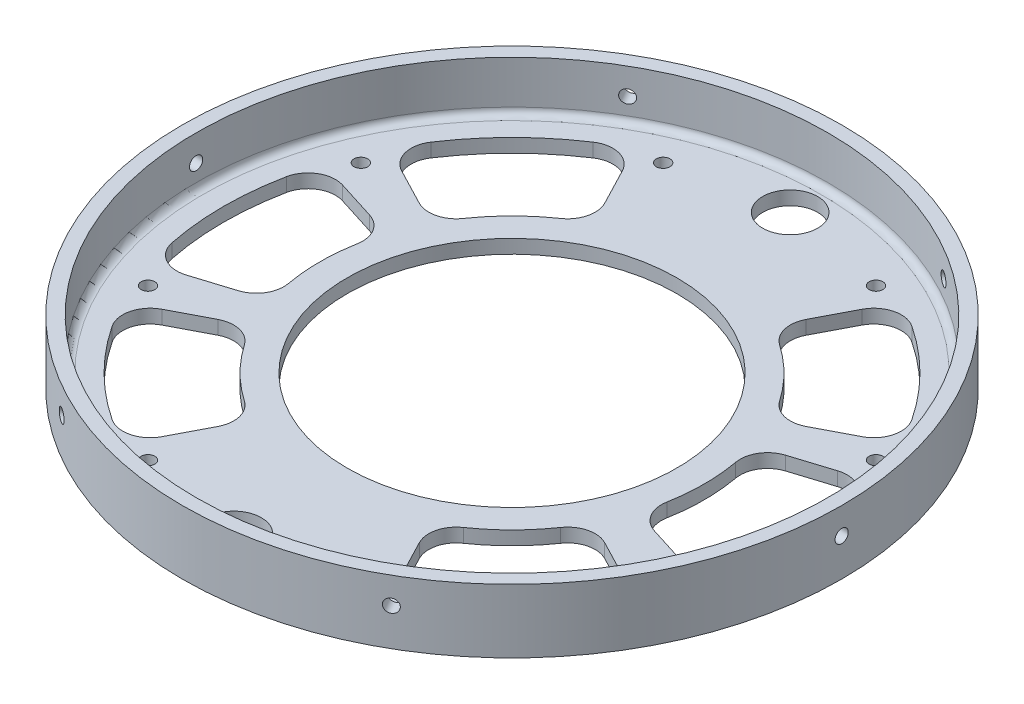
SolidWorks part; units mm, degrees
material "6061-T6 (SS)"
ref_plane "Front Plane" through (0, 0, 0) normal (0, 0, 1) x (1, 0, 0)
ref_plane "Top Plane" through (0, 0, 0) normal (0, 1, 0) x (1, 0, 0)
ref_plane "Right Plane" through (0, 0, 0) normal (1, 0, 0) x (0, 0, -1)
sketch "Sketch1" plane through (0, 0, 0) normal (0, 1, 0) x (1, 0, 0)
  circle A0 centre (0, 0) radius 76.2
extrude "Boss-Extrude1" add sketch "Sketch1" along normal blind 16.256
shell "Shell1" thickness 3.175
fillet "Fillet1" radius 1.5875 1 edges at (0, 3.175, 73.025)
sketch "Sketch2" plane through (0, 0, 0) normal (0, -1, 0) x (1, 0, 0)
  circle A0 centre (0, 0) radius 38.1
  dimension "D1" = 76.2
extrude "Cut-Extrude1" cut sketch "Sketch2" against normal blind 16.256
sketch "Sketch3" plane through (0, 0, 0) normal (1, 0, 0) x (0, 0, -1)
  line L0 (0, 0) -> (0, 8.636) construction
  circle A0 centre (0, 8.636) radius 1.524
  dimension "D2" = 3.048
  dimension "D1" = 8.636
extrude "Cut-Extrude2" cut sketch "Sketch3" against normal blind 76.2
pattern_circular "CirPattern1" count 6 over 360 about axis through (0, 16.256, 0) along (0, -1, 0) of "Cut-Extrude2"
sketch "Sketch5" plane through (0, 16.256, 0) normal (0, 1, 0) x (1, 0, 0)
  circle A0 centre (0, 0) radius 76.2
extrude "Cut-Extrude4" cut sketch "Sketch5" against normal blind 1.524
sketch "Sketch6" plane through (0, 3.175, 0) normal (0, 1, 0) x (1, 0, 0)
  line L0 (0, 0) -> (0, 71.4375) construction
  line L1 (0, 0) -> (61.8667, 35.7187) construction
  line L2 (0, 0) -> (61.8667, -35.7188) construction
  line L3 (0, 0) -> (0, -71.4375) construction
  line L4 (0, 0) -> (-61.8667, -35.7187) construction
  line L5 (0, 0) -> (-61.8667, 35.7188) construction
  circle A0 centre (0, 0) radius 71.4375 construction
  circle A1 centre (0, 0) radius 73.025 construction
  circle A2 centre (0, 64.2874) radius 6.35
  circle A3 centre (0, -64.2874) radius 6.35
  point P15 (0, 0)
  dimension "D2" = 64.2874
  dimension "D4" = 12.7
  dimension "D5" = 12.7
  dimension "D3" = 64.2874
  dimension "D1" = 6
extrude "Cut-Extrude5" cut sketch "Sketch6" against normal blind 12.7
sketch "Sketch7" plane through (0, 3.175, 0) normal (0, 1, 0) x (1, 0, 0)
  line L0 (0, 0) -> (0, 59.525) construction
  line L1 (24.6, 59.525) -> (-24.6, 59.525) construction
  line L2 (0, 0) -> (-76.2, 0) construction
  line L3 (24.6, -59.525) -> (-24.6, -59.525) construction
  line L4 (0, 0) -> (0, -59.525) construction
  line L5 (0, 0) -> (53.8815, 53.8815) construction
  line L6 (-59.525, 24.6) -> (-59.525, -24.6) construction
  line L7 (59.525, 24.6) -> (59.525, -24.6) construction
  line L8 (-59.525, 0) -> (59.525, 0) construction
  circle A0 centre (-24.6, 59.525) radius 1.5875
  circle A1 centre (24.6, 59.525) radius 1.5875
  circle A2 centre (0, 0) radius 76.2 construction
  circle A3 centre (24.6, -59.525) radius 1.5875
  circle A4 centre (-24.6, -59.525) radius 1.5875
  circle A5 centre (-59.525, -24.6) radius 1.5875
  circle A6 centre (-59.525, 24.6) radius 1.5875
  circle A7 centre (59.525, 24.6) radius 1.5875
  circle A8 centre (59.525, -24.6) radius 1.5875
  dimension "D1" = 3.175
  dimension "D2" = 24.6
  dimension "D3" = 59.525
extrude "Cut-Extrude6" cut sketch "Sketch7" against normal blind 6.35
sketch "Sketch9" plane through (0, 3.175, 0) normal (0, 1, 0) x (1, 0, 0)
  line L0 (-76.2, 0) -> (76.2, 0) construction
  line L1 (0, 76.2) -> (0, -76.2) construction
  line L2 (-27.7002, 53.2117) -> (-23.2729, 44.7067)
  line L3 (0, 0) -> (-67.5902, 35.1852) construction
  line L4 (0, 0) -> (-35.1852, 67.5902) construction
  line L5 (-44.7067, 23.2729) -> (-53.2117, 27.7002)
  line L6 (44.7067, 23.2729) -> (53.2117, 27.7002)
  line L7 (27.7002, 53.2117) -> (23.2729, 44.7067)
  line L8 (27.7002, -53.2117) -> (23.2729, -44.7067)
  line L9 (44.7067, -23.2729) -> (53.2117, -27.7002)
  line L10 (-44.7067, -23.2729) -> (-53.2117, -27.7002)
  line L11 (-27.7002, -53.2117) -> (-23.2729, -44.7067)
  circle A0 centre (0, 0) radius 76.2 construction
  circle A1 centre (0, 0) radius 38.1 construction
  circle A2 centre (0, 0) radius 71.4375 construction
  arc A3 (-25.2922, 36.5528) -> (-36.5528, 25.2922) centre (0, 0) ccw
  arc A4 (-36.8415, 55.5721) -> (-55.5721, 36.8415) centre (0, 0) ccw
  circle A5 centre (0, 0) radius 73.025 construction
  arc A6 (-53.2117, 27.7002) -> (-55.5721, 36.8415) centre (-50.2796, 33.3328) cw
  arc A7 (-44.7067, 23.2729) -> (-36.5528, 25.2922) centre (-41.7746, 28.9054) ccw
  arc A8 (-23.2729, 44.7067) -> (-25.2922, 36.5528) centre (-28.9054, 41.7746) cw
  arc A9 (-27.7002, 53.2117) -> (-36.8415, 55.5721) centre (-33.3328, 50.2796) ccw
  arc A10 (27.7002, 53.2117) -> (36.8415, 55.5721) centre (33.3328, 50.2796) cw
  arc A11 (23.2729, 44.7067) -> (25.2922, 36.5528) centre (28.9054, 41.7746) ccw
  arc A12 (44.7067, 23.2729) -> (36.5528, 25.2922) centre (41.7746, 28.9054) cw
  arc A13 (53.2117, 27.7002) -> (55.5721, 36.8415) centre (50.2796, 33.3328) ccw
  arc A14 (36.8415, 55.5721) -> (55.5721, 36.8415) centre (0, 0) cw
  arc A15 (25.2922, 36.5528) -> (36.5528, 25.2922) centre (0, 0) cw
  arc A16 (25.2922, -36.5528) -> (36.5528, -25.2922) centre (0, 0) ccw
  arc A17 (36.8415, -55.5721) -> (55.5721, -36.8415) centre (0, 0) ccw
  arc A18 (53.2117, -27.7002) -> (55.5721, -36.8415) centre (50.2796, -33.3328) cw
  arc A19 (44.7067, -23.2729) -> (36.5528, -25.2922) centre (41.7746, -28.9054) ccw
  arc A20 (23.2729, -44.7067) -> (25.2922, -36.5528) centre (28.9054, -41.7746) cw
  arc A21 (27.7002, -53.2117) -> (36.8415, -55.5721) centre (33.3328, -50.2796) ccw
  arc A22 (-27.7002, -53.2117) -> (-36.8415, -55.5721) centre (-33.3328, -50.2796) cw
  arc A23 (-23.2729, -44.7067) -> (-25.2922, -36.5528) centre (-28.9054, -41.7746) ccw
  arc A24 (-44.7067, -23.2729) -> (-36.5528, -25.2922) centre (-41.7746, -28.9054) cw
  arc A25 (-53.2117, -27.7002) -> (-55.5721, -36.8415) centre (-50.2796, -33.3328) ccw
  arc A26 (-36.8415, -55.5721) -> (-55.5721, -36.8415) centre (0, 0) cw
  arc A27 (-25.2922, -36.5528) -> (-36.5528, -25.2922) centre (0, 0) cw
  point P21 (-59.1414, 30.7871)
  point P24 (-39.4276, 20.5247)
  point P41 (39.4276, 20.5247)
  point P42 (59.1414, 30.7871)
  point P55 (59.1414, -30.7871)
  point P56 (39.4276, -20.5247)
  point P69 (-39.4276, -20.5247)
  point P70 (-59.1414, -30.7871)
  dimension "D3" = 76.2
  dimension "D4" = 142.875
  dimension "D5" = 6.35
  dimension "D6" = 6.35
  dimension "D8" = 6.35
  dimension "D1" = 27.5
  dimension "D2" = 27.5
  dimension "D7" = 27.5
extrude "Cut-Extrude8" cut sketch "Sketch9" against normal blind 6.35
sketch "Sketch11" plane through (0, 3.175, 0) normal (0, 1, 0) x (1, 0, 0)
  line L0 (0, 0) -> (-76.2, 0) construction
  line L1 (0, 0) -> (76.2, 0) construction
  line L2 (-48.0688, 15.156) -> (-57.2133, 18.0393)
  line L3 (-48.0688, -15.156) -> (-57.2133, -18.0393)
  line L4 (0, 0) -> (-53.8815, 53.8815) construction
  line L5 (0, 0) -> (0, 76.2) construction
  line L6 (0, 0) -> (-48.9592, 25.4865) construction
  line L7 (-53.2117, 27.7002) -> (-44.7067, 23.2729) construction
  line L8 (0, 0) -> (-25.4865, 48.9592) construction
  line L9 (-23.2729, 44.7067) -> (-27.7002, 53.2117) construction
  line L10 (48.0688, -15.156) -> (57.2133, -18.0393)
  line L11 (48.0688, 15.156) -> (57.2133, 18.0393)
  arc A0 (-43.731, 7.9624) -> (-43.731, -7.9624) centre (0, 0) ccw
  arc A1 (-65.3463, 13.2446) -> (-65.3463, -13.2446) centre (0, 0) ccw
  circle A2 centre (0, 0) radius 76.2 construction
  arc A3 (-57.2133, -18.0393) -> (-65.3463, -13.2446) centre (-59.1228, -11.9832) cw
  arc A4 (-43.731, -7.9624) -> (-48.0688, -15.156) centre (-49.9783, -9.0999) cw
  arc A5 (-43.731, 7.9624) -> (-48.0688, 15.156) centre (-49.9783, 9.0999) ccw
  arc A6 (-57.2133, 18.0393) -> (-65.3463, 13.2446) centre (-59.1228, 11.9832) ccw
  arc A7 (57.2133, 18.0393) -> (65.3463, 13.2446) centre (59.1228, 11.9832) cw
  arc A8 (43.731, 7.9624) -> (48.0688, 15.156) centre (49.9783, 9.0999) cw
  arc A9 (43.731, -7.9624) -> (48.0688, -15.156) centre (49.9783, -9.0999) ccw
  arc A10 (57.2133, -18.0393) -> (65.3463, -13.2446) centre (59.1228, -11.9832) ccw
  arc A11 (65.3463, 13.2446) -> (65.3463, -13.2446) centre (0, 0) cw
  arc A12 (43.731, 7.9624) -> (43.731, -7.9624) centre (0, 0) cw
  point P21 (-63.5891, -20.0496)
  point P24 (-42.3927, -13.3664)
  point P27 (-42.3927, 13.3664)
  point P30 (-63.5891, 20.0496)
  point P43 (63.5891, 20.0496)
  point P44 (42.3927, 13.3664)
  point P45 (42.3927, -13.3664)
  point P46 (63.5891, -20.0496)
  dimension "D1" = 88.9
  dimension "D2" = 133.35
  dimension "D9" = 6.35
  dimension "D3" = 135
  dimension "D4" = 17.5
  dimension "D5" = 17.5
  dimension "D6" = 17.5
  dimension "D7" = 22.225
  dimension "D8" = 22.225
extrude "Cut-Extrude9" cut sketch "Sketch11" against normal blind 6.35 contours L2 A1 L3 A0 | A8 A12 A9 L10 A10 A11 A7 L11
